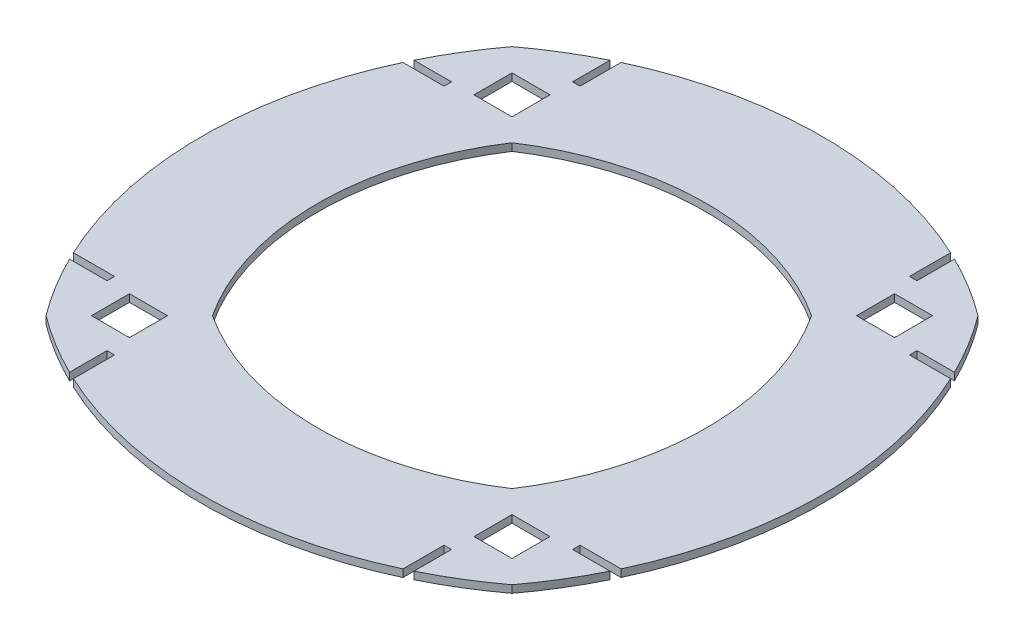
SolidWorks part; units mm, degrees
ref_plane "Front Plane" through (0, 0, 0) normal (0, 0, 1) x (1, 0, 0)
ref_plane "Top Plane" through (0, 0, 0) normal (0, 1, 0) x (1, 0, 0)
ref_plane "Right Plane" through (0, 0, 0) normal (1, 0, 0) x (0, 0, -1)
sketch "Sketch1" plane through (0, 0, 0) normal (0, 1, 0) x (1, 0, 0)
  line L0 (115, 140.4) -> (115, 115)
  line L1 (-155.565, 155.565) -> (155.565, 155.565) construction
  line L2 (-155.565, 155.565) -> (-155.565, -155.565) construction
  line L3 (-155.565, -155.565) -> (155.565, -155.565) construction
  line L4 (155.565, 155.565) -> (155.565, -155.565) construction
  line L5 (0, -155.565) -> (0, 155.565) construction
  line L6 (-155.565, 0) -> (155.565, 0) construction
  line L7 (-140.4, 140.4) -> (140.4, 140.4) construction
  line L8 (-140.4, 140.4) -> (-140.4, -140.4) construction
  line L9 (-140.4, -140.4) -> (140.4, -140.4) construction
  line L10 (140.4, 140.4) -> (140.4, -140.4) construction
  line L11 (0, -140.4) -> (0, 140.4) construction
  line L12 (-140.4, 0) -> (140.4, 0) construction
  line L13 (-140.4, 140.4) -> (-115, 140.4)
  line L14 (-140.4, 140.4) -> (-140.4, 115)
  line L15 (-140.4, 115) -> (-115, 115)
  line L16 (-115, 140.4) -> (-115, 115)
  line L17 (140.4, 140.4) -> (115, 140.4)
  line L18 (140.4, 140.4) -> (140.4, 115)
  line L19 (140.4, 115) -> (115, 115)
  line L20 (140.4, -140.4) -> (140.4, -115)
  line L21 (140.4, -140.4) -> (115, -140.4)
  line L22 (115, -140.4) -> (115, -115)
  line L23 (140.4, -115) -> (115, -115)
  line L24 (-115, -140.4) -> (-115, -115)
  line L25 (-140.4, -140.4) -> (-115, -140.4)
  line L26 (-140.4, -140.4) -> (-140.4, -115)
  line L27 (-140.4, -115) -> (-115, -115)
  line L28 (115, 155.4) -> (110, 155.4)
  line L29 (-115, 155.4) -> (-110, 155.4)
  line L30 (-115, 155.4) -> (-115, 180.4239)
  line L31 (110, 155.4) -> (110, 182.8238)
  line L32 (-110, 155.4) -> (-110, 182.8238)
  line L33 (-155.4, 115) -> (-180.4239, 115)
  line L34 (-155.4, 115) -> (-155.4, 110)
  line L35 (-155.4, 110) -> (-182.8238, 110)
  line L36 (115, 155.4) -> (115, 180.4239)
  line L37 (155.4, 115) -> (155.4, 110)
  line L38 (155.4, 115) -> (180.4239, 115)
  line L39 (155.4, 110) -> (182.8238, 110)
  line L40 (155.4, -115) -> (155.4, -110)
  line L41 (155.4, -110) -> (182.8238, -110)
  line L42 (155.4, -115) -> (180.4239, -115)
  line L43 (115, -155.4) -> (110, -155.4)
  line L44 (115, -155.4) -> (115, -180.4239)
  line L45 (110, -155.4) -> (110, -182.8238)
  line L46 (-115, -155.4) -> (-110, -155.4)
  line L47 (-110, -155.4) -> (-110, -182.8238)
  line L48 (-115, -155.4) -> (-115, -180.4239)
  line L49 (-155.4, -115) -> (-155.4, -110)
  line L50 (-155.4, -115) -> (-180.4239, -115)
  line L51 (-155.4, -110) -> (-182.8238, -110)
  line L53 (-100, 100) -> (100, 100) construction
  line L54 (-100, 100) -> (-100, -100) construction
  line L55 (-100, -100) -> (100, -100) construction
  line L56 (100, 100) -> (100, -100) construction
  line L57 (0, -100) -> (0, 100) construction
  line L58 (-100, 0) -> (100, 0) construction
  arc A0 (-155.565, 155.565) -> (-115, 180.4239) centre (0, -52.7605) cw
  arc A1 (155.565, 155.565) -> (180.4239, 115) centre (-52.7605, 0) cw
  arc A2 (155.565, -155.565) -> (115, -180.4239) centre (0, 52.7605) cw
  arc A3 (-155.565, -155.565) -> (-180.4239, -115) centre (52.7605, 0) cw
  arc A4 (-180.4239, 115) -> (-155.565, 155.565) centre (52.7605, 0) cw
  arc A5 (-110, 182.8238) -> (110, 182.8238) centre (0, -52.7605) cw
  arc A6 (115, 180.4239) -> (155.565, 155.565) centre (0, -52.7605) cw
  arc A7 (182.8238, 110) -> (182.8238, -110) centre (-52.7605, 0) cw
  arc A8 (180.4239, -115) -> (155.565, -155.565) centre (-52.7605, 0) cw
  arc A9 (110, -182.8238) -> (-110, -182.8238) centre (0, 52.7605) cw
  arc A10 (-115, -180.4239) -> (-155.565, -155.565) centre (0, 52.7605) cw
  arc A11 (-182.8238, -110) -> (-182.8238, 110) centre (52.7605, 0) cw
  arc A12 (-100, 100) -> (100, 100) centre (0, -52.7605) cw
  arc A13 (100, 100) -> (100, -100) centre (-52.7605, 0) cw
  arc A14 (100, -100) -> (-100, -100) centre (0, 52.7605) cw
  arc A15 (-100, -100) -> (-100, 100) centre (52.7605, 0) cw
  point P0 (0, 0)
  point P8 (0, 0)
  point P56 (0, 0)
  dimension "D2" = 260
  dimension "D1" = 311.13
  dimension "D3" = 280.8
  dimension "D4" = 25.4
  dimension "D5" = 5
  dimension "D6" = 5
  dimension "D7" = 15
  dimension "D8" = 15
  dimension "D9" = 200
  dimension "D10" = 200
extrude "Boss-Extrude1" add sketch "Sketch1" along normal blind 5
